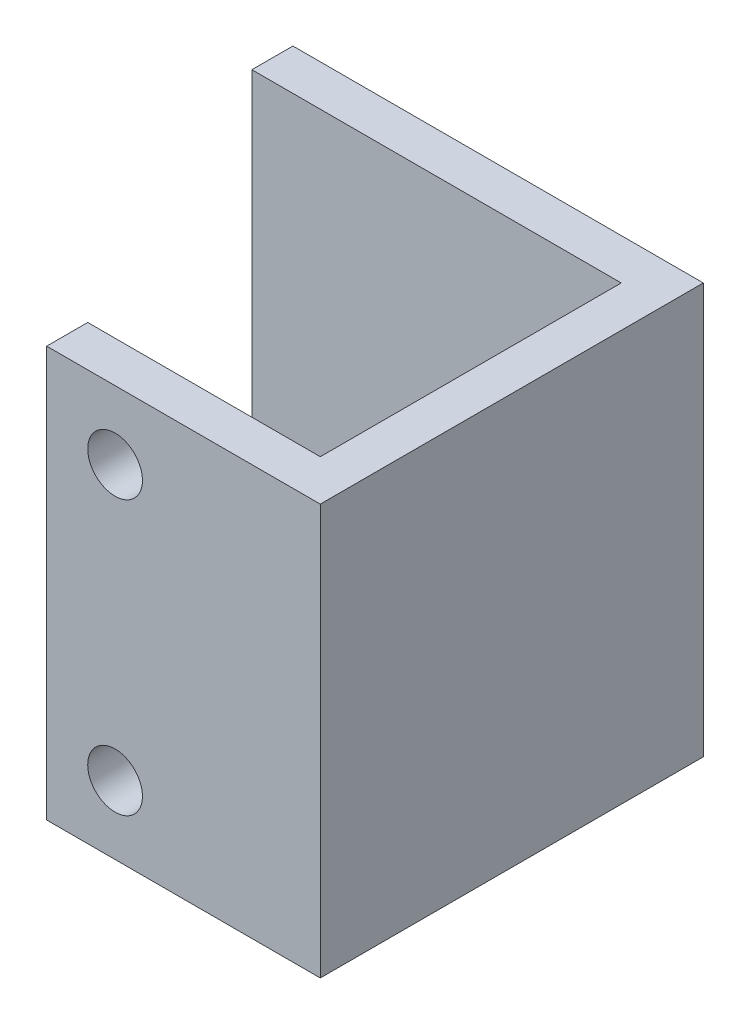
SolidWorks part; units mm, degrees
ref_plane "前视基准面" through (0, 0, 0) normal (0, 0, 1) x (1, 0, 0)
ref_plane "上视基准面" through (0, 0, 0) normal (0, 1, 0) x (1, 0, 0)
ref_plane "右视基准面" through (0, 0, 0) normal (1, 0, 0) x (0, 0, -1)
other "Configuration Table"
sketch "草图1" plane through (0, 0, 0) normal (0, 0, 1) x (1, 0, 0)
  line L1 (-15, -15) -> (15, -15)
  line L2 (-15, -15) -> (-15, 15)
  line L3 (-15, 15) -> (15, 15)
  line L4 (15, -15) -> (15, 15)
  line L5 (-15, -15) -> (15, 15) construction
  line L6 (-15, 15) -> (15, -15) construction
  point P0 (0, 0)
  dimension "D1" = 30
  dimension "D2" = 30
extrude "凸台-拉伸1" add sketch "草图1" along normal blind 3
sketch "草图2" plane through (0, 0, 3) normal (0, 0, 1) x (1, 0, 0)
  line L0 (-15, -15) -> (15, -15) construction
  line L1 (15, 15) -> (12, 15)
  line L2 (15, 15) -> (15, -15)
  line L3 (15, -15) -> (12, -15)
  line L4 (12, 15) -> (12, -15)
  dimension "D1" = 3
extrude "凸台-拉伸2" add sketch "草图2" along normal blind 22
sketch "草图3" plane through (0, 0, 25) normal (0, 0, 1) x (1, 0, 0)
  line L0 (-15, -15) -> (12, -15) construction
  line L1 (15, 15) -> (-5, 15)
  line L2 (15, 15) -> (15, -15)
  line L3 (15, -15) -> (-5, -15)
  line L4 (-5, 15) -> (-5, -15)
  line L5 (13.75, 0) -> (-13.75, 0) construction
  circle A0 centre (0, 10) radius 2
  circle A1 centre (0, -10) radius 2
  dimension "D2" = 4
  dimension "D1" = 20
  dimension "D3" = 5
  dimension "D4" = 5
extrude "凸台-拉伸3" add sketch "草图3" along normal blind 3
